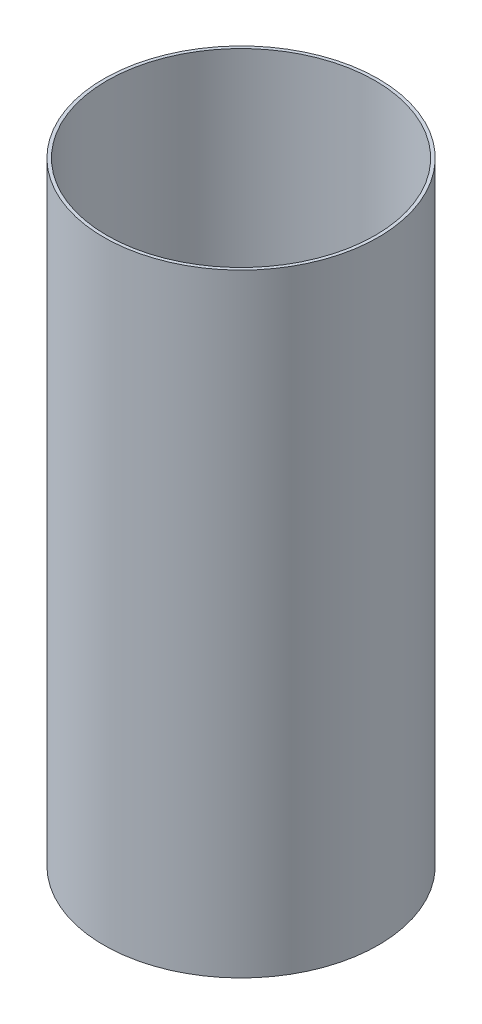
SolidWorks part; units mm, degrees
material "A-Glass Fiber"
ref_plane "Front Plane" through (0, 0, 0) normal (0, 0, 1) x (1, 0, 0)
ref_plane "Top Plane" through (0, 0, 0) normal (0, 1, 0) x (1, 0, 0)
ref_plane "Right Plane" through (0, 0, 0) normal (1, 0, 0) x (0, 0, -1)
sketch "Sketch1" plane through (0, 0, 0) normal (0, 1, 0) x (1, 0, 0)
  circle A0 centre (0, 0) radius 68.2625
  circle A1 centre (0, 0) radius 66.675
  dimension "D1" = 136.525
  dimension "D2" = 133.35
extrude "Boss-Extrude1" add sketch "Sketch1" along normal blind 304.8 contours A1 | A0
equation "\"Length\"= 12"
equation "\"D1@Boss-Extrude1\"=\"Length\""
